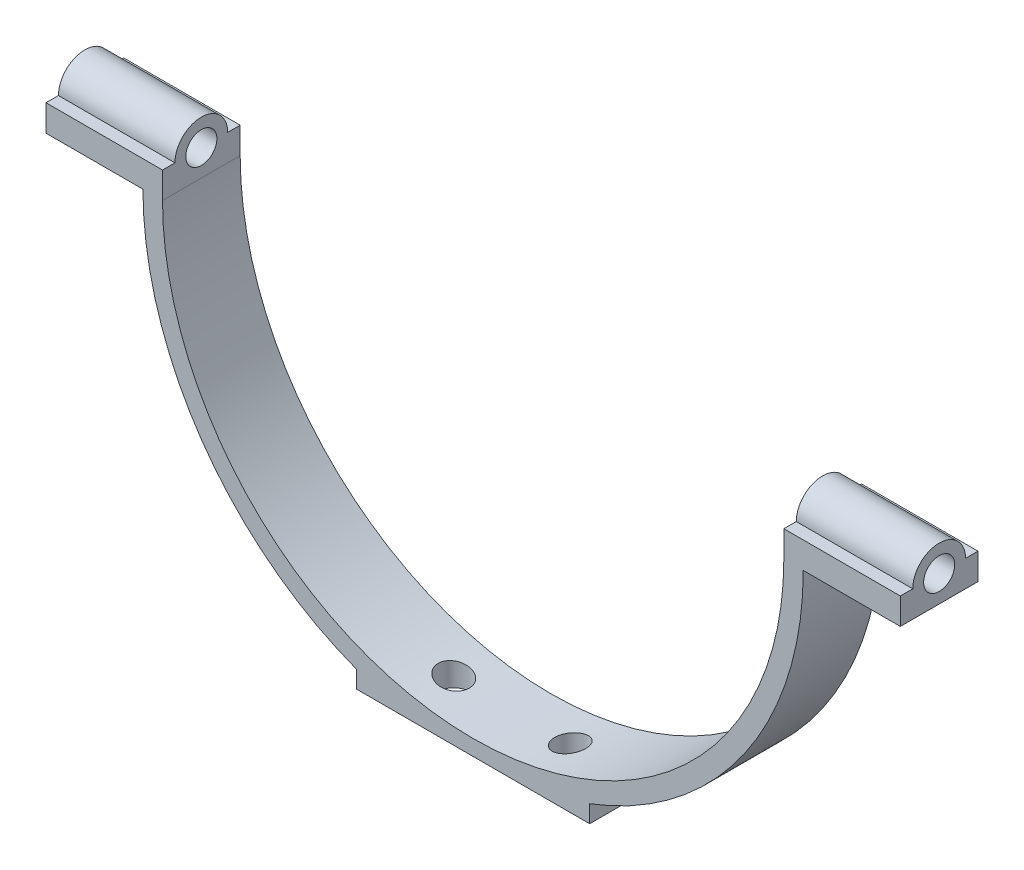
SolidWorks part; units mm, degrees
ref_plane "Front Plane" through (0, 0, 0) normal (0, 0, 1) x (1, 0, 0)
ref_plane "Top Plane" through (0, 0, 0) normal (0, 1, 0) x (1, 0, 0)
ref_plane "Right Plane" through (0, 0, 0) normal (1, 0, 0) x (0, 0, -1)
sketch "Sketch1" plane through (0, 0, 0) normal (0, 0, 1) x (1, 0, 0)
  line L0 (0, -53.34) -> (19.05, -53.34)
  line L1 (19.05, -53.34) -> (19.05, -50.5015)
  line L2 (0, 0) -> (0, -53.34) construction
  line L3 (0, -53.34) -> (-19.05, -53.34)
  line L4 (-19.05, -53.34) -> (-19.05, -50.5286)
  line L5 (-54.0004, 0) -> (-50.8, 0)
  line L6 (50.8, 0) -> (53.975, 0)
  circle A0 centre (0, 0) radius 50.8 construction
  arc A1 (-50.8, 0) -> (50.8, 0) centre (0, 0) ccw
  arc A2 (19.05, -50.5015) -> (53.975, 0) centre (0, 0) ccw
  arc A3 (-19.05, -50.5286) -> (-54.0004, 0) centre (0, 0) cw
  point P12 (0, -50.8)
  dimension "D1" = 101.6
  dimension "D3" = 3.175
  dimension "D4" = 3.2004
  dimension "D2" = 2.54
  dimension "D5" = 19.05
  dimension "D6" = 19.05
extrude "Boss-Extrude1" add sketch "Sketch1" along normal mid plane 12.7
ref_plane "Plane1" through (50.8, 0, 0) normal (1, 0, 0) x (0, 0, -1)
sketch "Sketch2" plane through (50.8, 0, 0) normal (1, 0, 0) x (0, 0, -1)
  line L0 (0, 0) -> (0, 4.318) construction
  line L1 (-6.35, 0) -> (6.35, 0) construction
  line L3 (-6.35, 0) -> (6.35, 0)
  line L5 (-6.35, 0) -> (-6.35, 4.318)
  line L6 (-6.35, 4.318) -> (-4.318, 4.318)
  line L7 (4.318, 4.318) -> (6.35, 4.318)
  line L8 (6.35, 4.318) -> (6.35, 0)
  line L9 (-6.35, 0) -> (-6.35, -50.5015) construction
  circle A0 centre (0, 4.318) radius 2.54
  circle A1 centre (0, 4.318) radius 4.318 construction
  arc A2 (4.318, 4.318) -> (-4.318, 4.318) centre (0, 4.318) ccw
  point P10 (-6.4338, 0)
  point P13 (-6.35, 0)
  dimension "D1" = 5.08
  dimension "D2" = 1.778
extrude "Boss-Extrude2" add sketch "Sketch2" along normal blind 19.05
mirror "Mirror1" about plane through (0, 0, 0) normal (1, 0, 0) of "Boss-Extrude2"
sketch "Sketch3" plane through (0, -53.34, 0) normal (0, -1, 0) x (1, 0, 0)
  line L0 (-9.525, 0) -> (0, 0) construction
  line L1 (0, 0) -> (9.525, 0) construction
  circle A0 centre (-9.525, 0) radius 2.54
  circle A1 centre (9.525, 0) radius 2.54
  dimension "D2" = 5.08
  dimension "D3" = 5.08
  dimension "D1" = 19.05
extrude "Cut-Extrude1" cut sketch "Sketch3" against normal blind 19.05
